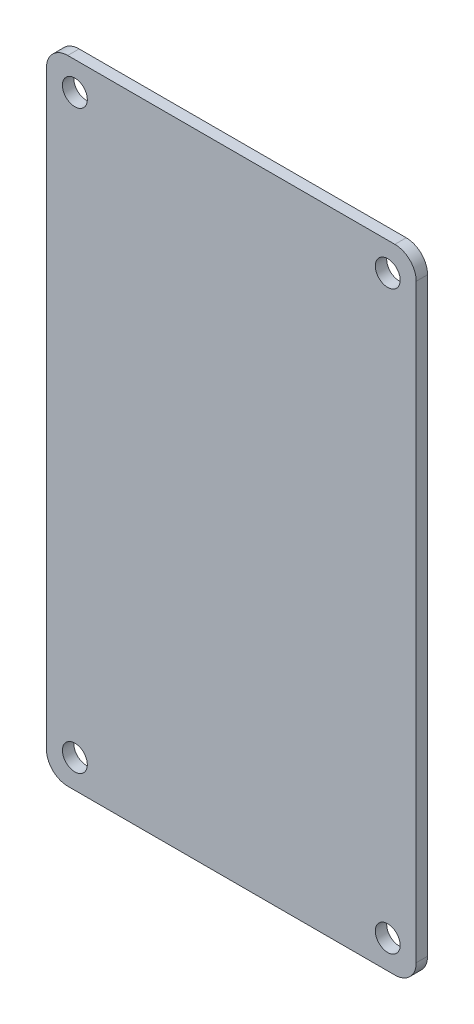
SolidWorks part; units mm, degrees
ref_plane "Plan de face" through (0, 0, 0) normal (0, 0, 1) x (1, 0, 0)
ref_plane "Plan de dessus" through (0, 0, 0) normal (0, 1, 0) x (1, 0, 0)
ref_plane "Plan de droite" through (0, 0, 0) normal (1, 0, 0) x (0, 0, -1)
sketch "Esquisse1" plane through (0, 0, 0) normal (0, 0, 1) x (1, 0, 0)
  line L1 (0, 0) -> (52, 0)
  line L2 (0, 0) -> (0, 89)
  line L3 (0, 89) -> (52, 89)
  line L4 (52, 0) -> (52, 89)
  dimension "D1" = 52
  dimension "D2" = 89
extrude "Boss.-Extru.1" add sketch "Esquisse1" along normal blind 1.6
sketch "Esquisse2" plane through (0, 0, 1.6) normal (0, 0, 1) x (1, 0, 0)
  line L0 (26, 0) -> (26, 89) construction
  line L1 (0, 0) -> (52, 0) construction
  line L2 (52, 89) -> (0, 89) construction
  line L3 (52, 44.5) -> (0, 44.5) construction
  line L4 (52, 0) -> (52, 89) construction
  line L5 (0, 89) -> (0, 0) construction
  circle A0 centre (48, 85) radius 1.75
  circle A1 centre (48, 4) radius 1.75
  circle A2 centre (4, 4) radius 1.75
  circle A3 centre (4, 85) radius 1.75
  dimension "D1" = 81
  dimension "D2" = 44
  dimension "D3" = 3.5
extrude "Enlèv. mat.-Extru.1" cut sketch "Esquisse2" against normal through all both and the other way through all
fillet "Congé1" radius 3 4 edges at (0, 0, 0.8) (52, 0, 0.8) (52, 89, 0.8) (0, 89, 0.8)
